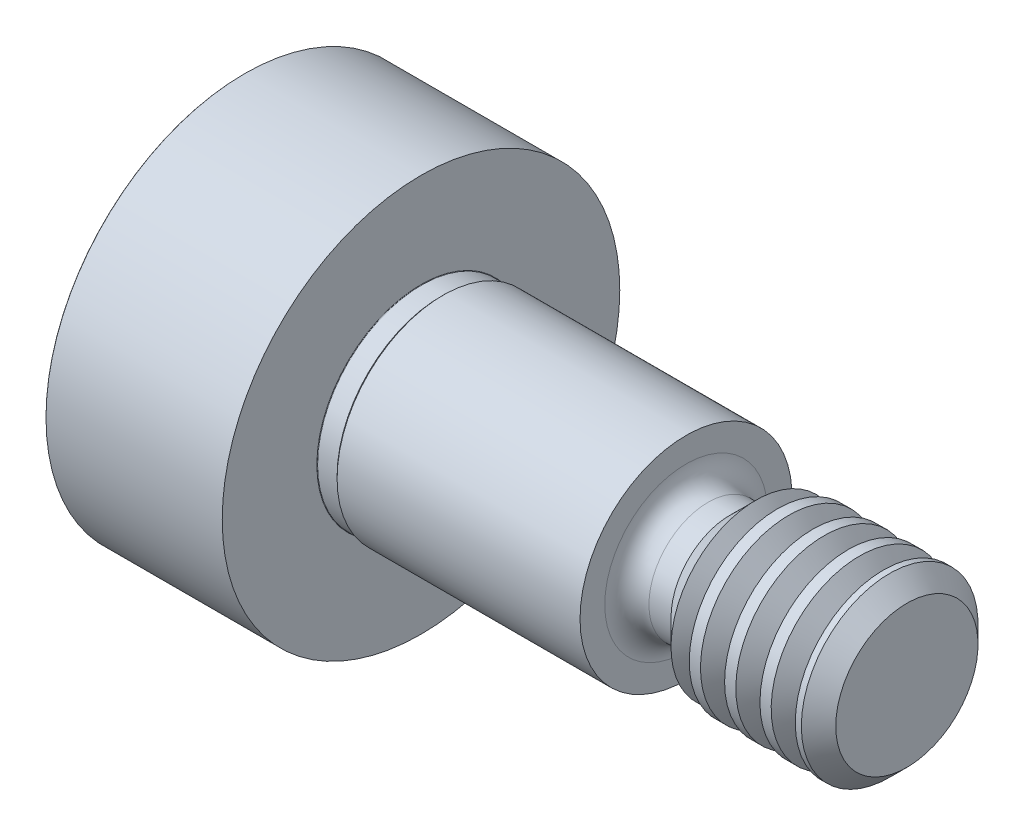
SolidWorks part; units mm, degrees
ref_plane "Plane1" through (0, 0, 0) normal (0, 0, 1) x (1, 0, 0)
ref_plane "Plane2" through (0, 0, 0) normal (0, 1, 0) x (1, 0, 0)
ref_plane "Plane3" through (0, 0, 0) normal (1, 0, 0) x (0, 0, -1)
sketch "BodySke" plane through (0, 0, 0) normal (0, 0, 1) x (1, 0, 0)
  line L0 (0, 0) -> (0, 4.5)
  line L2 (0, 4.5) -> (4, 4.5)
  line L3 (4, 4.5) -> (4, 2.36)
  line L4 (4.01, 2.35) -> (4.45, 2.35)
  line L5 (4.45, 2.35) -> (4.5, 2.4)
  line L6 (4.5, 2.4) -> (10, 2.4)
  line L7 (10, 2.4) -> (10, 1.84)
  line L8 (10.5, 1.34) -> (11, 1.34)
  line L9 (11, 1.34) -> (11.66, 2)
  line L10 (11.66, 2) -> (14.61, 2)
  line L11 (14.61, 2) -> (15, 1.61)
  line L12 (15, 1.61) -> (15, 0)
  line L13 (15, 0) -> (0, 0)
  line L14 (-6.35, 0) -> (107.95, 0) construction
  line L15 (14.61, -2) -> (15, -1.61) construction
  line L16 (10, -1.34) -> (11, -1.34) construction
  line L17 (4.5, -2.4) -> (10, -2.4) construction
  line L18 (4, -2.35) -> (4.45, -2.35) construction
  line L20 (11.8, 6.1914) -> (11.8, -11.1614) construction
  line L21 (11, 5.3861) -> (11, -10.4635) construction
  arc A0 (10, 1.84) -> (10.5, 1.34) centre (10.5, 1.84) ccw
  arc A1 (4.01, 2.35) -> (4, 2.36) centre (4.01, 2.36) cw
  point P29 (10, 1.34)
  point P32 (4, 2.35)
  dimension "Thread_neck_fillet_rad" = 0.5
  dimension "Head_fillet_radius" = 0.01
  dimension "Head_dia" = 9
  dimension "Head_ht" = 4
  dimension "Shoulder_neck_dia" = 4.7
  dimension "Diameter" = 4.8
  dimension "Thread_dia" = 4
  dimension "Minor_dia" = 3.22
  dimension "Thread_ch_ang" = 45
  dimension "Thread_neck_dia" = 2.68
  dimension "D11" = 45
  dimension "Thread_length" = 5
  dimension "D13" = 45
  dimension "Length" = 6
  dimension "Thread_neck_width" = 1
  dimension "Shoulder_neck_width" = 0.5
  dimension "Advance" = 0.8
  dimension "Thread_nom" = 4
  dimension "Thread_lim" = 3.2
revolve "BaseBody" add sketch "BodySke" angle 360 about L14
cosmetic thread "ThreadCosmetic" [suppressed] parameters "Thread_length"=3.2, "Thread_minor"=3.22
chamfer "Chamfer1" distance 0.01 1 edges at (0, 0, 4.5)
sketch "Sketch2" plane through (0, 0, 0) normal (0, 0, 1) x (1, 0, 0)
  line L0 (0, 1.04) -> (2, 1.04)
  line L1 (2, 1.04) -> (2.6004, 0)
  line L3 (2.6004, 0) -> (0, 0)
  line L4 (0, 0) -> (0, 1.04)
  line L5 (0, -1.04) -> (2, -1.04) construction
  line L6 (0, 0) -> (47.625, 0) construction
  dimension "D2" = 60
  dimension "PreBroach_depth" = 2
  dimension "PreBroach_dia" = 2.08
revolve "PreBroach" cut sketch "Sketch2" angle 360 about L6
sketch "Sketch3" plane through (0, 0, 0) normal (-1, 0, 0) x (0, 0, 1)
  line L0 (-1.04, -0.6004) -> (-1.04, 0.6004)
  line L1 (-1.04, 0.6004) -> (0, 1.2009)
  line L2 (0, 1.2009) -> (1.04, 0.6004)
  line L3 (1.04, 0.6004) -> (1.04, -0.6004)
  line L4 (1.04, -0.6004) -> (0, -1.2009)
  line L5 (0, -1.2009) -> (-1.04, -0.6004)
  dimension "D1" = 1.04
  dimension "Hex_size" = 2.08
  dimension "D2" = 1.04
  dimension "D3" = 120
  dimension "D4" = 2.08
extrude "Hex" cut sketch "Sketch3" against normal blind 2.4
sketch "ThdSchSke" plane through (0, 0, 0) normal (0, 0, 1) x (1, 0, 0)
  line L0 (11.8, -1.61) -> (11.2468, -2.4)
  line L1 (11.8, -1.61) -> (12.3532, -2.4)
  line L2 (12.3532, -2.4) -> (12.3532, -3)
  line L3 (-3.175, 0) -> (5.1513, 0) construction
  line L5 (12.3532, -3) -> (11.2468, -3)
  line L6 (11.2468, -3) -> (11.2468, -2.4)
  dimension "Thread_minor" = 3.22
  dimension "Diameter" = 4.8
  dimension "Start" = 11.8
  dimension "SideAngle" = 55
  dimension "VeeAngle" = 70
  dimension "Overcut" = 6
revolve "ThreadSchematic" cut sketch "ThdSchSke" angle 360 about L3
pattern_linear "ThdSchPat" count 4 spacing 0.8 along (1, 0, 0) of "ThreadSchematic"
equation "\"Thread_minor@ThreadCosmetic\" = \"Minor_dia@BodySke\""
equation "\"D1@Sketch3\" = \"Hex_size@Sketch3\" / 2"
equation "\"D2@Sketch3\" = \"D1@Sketch3\""
equation "\"D4@Sketch3\" = \"Hex_size@Sketch3\""
equation "\"Width@Chamfer1\" = \"Head_fillet_radius@BodySke\""
equation "\"Thread_length@ThreadCosmetic\" = ((sgn( (\"Thread_length@BodySke\" - \"Advance@BodySke\" - \"Thread_neck_width@BodySke\" ) - \"Thread_nom@BodySke\" )-1)*( (\"Thread_length@BodySke\" - \"Advance@BodySke\" - \"Thread_neck_width@BodySke\" ) - \"Thread_nom@BodySke\" ))/-2+ \"Thread_nom@BodySke\""
equation "\"Thread_minor@ThdSchSke\" = \"Minor_dia@BodySke\""
equation "\"Diameter@ThdSchSke\" = \"Diameter@BodySke\""
equation "\"Overcut@ThdSchSke\" = \"Diameter@BodySke\" * 1.25"
equation "\"Start@ThdSchSke\" = \"Head_ht@BodySke\" + \"Length@BodySke\" + \"Thread_length@BodySke\" -  \"Thread_length@ThreadCosmetic\"  '---Non-countersunk---"
equation "\"Num_threads@ThdSchPat\" = int( \"Thread_length@ThreadCosmetic\" / \"Advance@BodySke\" + 0.999 ) + 1"
equation "\"Advance@ThdSchPat\" = \"Thread_length@ThreadCosmetic\" /  (\"Num_threads@ThdSchPat\" - 1) 'relax it"
equation "\"Num_threads@ThdSchPat\" = \"Num_threads@ThdSchPat\" - sgn( \"Num_threads@ThdSchPat\" - 1) '---chamfered tips only---"
